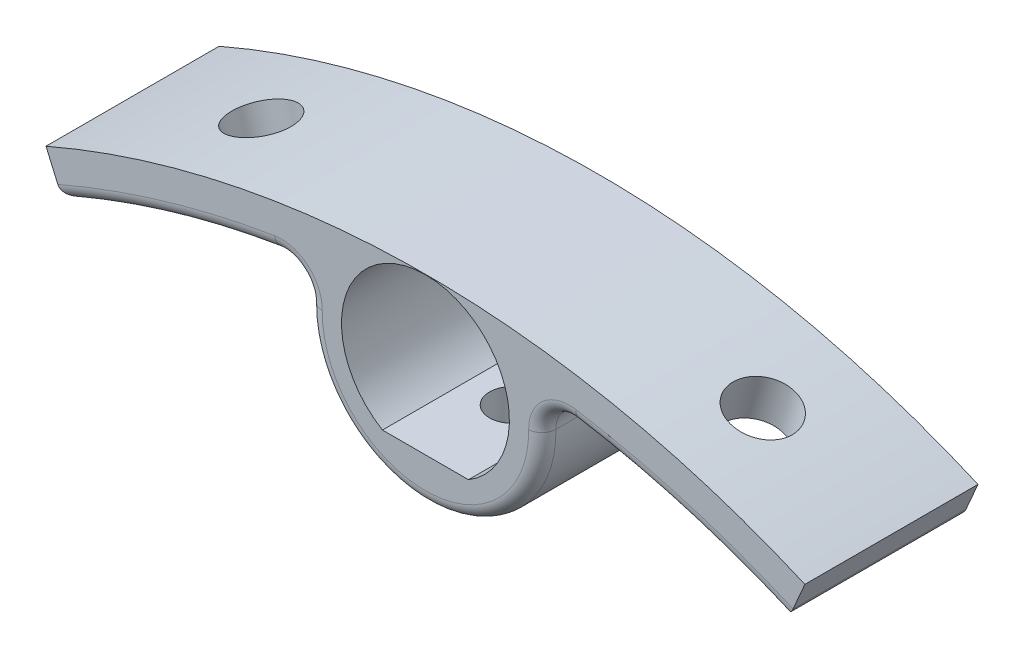
SolidWorks part; units mm, degrees
ref_plane "Front Plane" through (0, 0, 0) normal (0, 0, 1) x (1, 0, 0)
ref_plane "Top Plane" through (0, 0, 0) normal (0, 1, 0) x (1, 0, 0)
ref_plane "Right Plane" through (0, 0, 0) normal (1, 0, 0) x (0, 0, -1)
sketch "Sketch1" plane through (0, 0, 0) normal (0, 0, 1) x (1, 0, 0)
  line L0 (0, 0) -> (0, -69.85) construction
  line L1 (0, -6.1913) -> (0, -0.7937) construction
  line L2 (-2.765, -10.8267) -> (2.765, -10.8267)
  line L3 (-27.8391, -5.7875) -> (-26.5737, -8.6994)
  line L4 (27.8391, -5.7875) -> (26.5737, -8.6994)
  arc A0 (-27.8391, -5.7875) -> (27.8391, -5.7875) centre (0, -69.85) cw
  arc A1 (2.765, -10.8267) -> (-2.765, -10.8267) centre (0, -6.1913) ccw
  arc A4 (-8.1967, -3.6807) -> (8.1967, -3.6807) centre (0, -6.1913) ccw
  arc A5 (-8.1967, -3.6807) -> (-26.5737, -8.6994) centre (0, -69.85) ccw
  arc A6 (8.1967, -3.6807) -> (26.5737, -8.6994) centre (0, -69.85) cw
  point P9 (0, -14.7637)
  dimension "D1" = 69.85
  dimension "D3" = 10.033
  dimension "D4" = 5.3975
  dimension "D5" = 3.175
  dimension "D7" = 3.175
  dimension "D2" = 0.7937
  dimension "D6" = 19.05
extrude "Boss-Extrude1" add sketch "Sketch1" along normal blind 12.7
sketch "Sketch2" plane through (0, -10.8267, 0) normal (0, 1, 0) x (1, 0, 0)
  line L0 (0, 0) -> (0, -12.7) construction
  line L1 (-27.8391, -12.7) -> (27.8391, -12.7) construction
  circle A0 centre (0, -6.35) radius 1.651
  dimension "D1" = 3.302
extrude "Cut-Extrude1" cut sketch "Sketch2" against normal through all
sketch "Sketch3" plane through (0, -10.8267, 0) normal (0, 1, 0) x (1, 0, 0)
  line L0 (27.8391, 0) -> (-27.8391, 0) construction
  line L1 (-1.5875, 0) -> (1.5875, 0)
  line L2 (-1.5875, 0) -> (-1.5875, -12.7)
  line L3 (-1.5875, -12.7) -> (1.5875, -12.7)
  line L4 (1.5875, 0) -> (1.5875, -12.7)
  line L5 (-27.8391, -12.7) -> (27.8391, -12.7) construction
  point P8 (0, 0)
  dimension "D1" = 3.175
extrude "Cut-Extrude2" [suppressed] cut sketch "Sketch3" along normal through all
ref_plane "Plane1" through (0.3665, -1.3422, 0) normal (-0.2634, 0.9647, 0) x (0.9647, 0.2634, 0)
sketch "Sketch4" plane through (0.3665, -1.3422, 0) normal (-0.2634, 0.9647, 0) x (0.9647, 0.2634, 0)
  line L0 (-27.9268, -6.35) -> (-8.8768, -6.35) construction
  line L1 (-27.9268, -12.7) -> (-27.9268, 0) construction
  line L2 (-8.8768, -12.7) -> (-8.8768, 0) construction
  circle A0 centre (-18.4018, -6.35) radius 2.253
  dimension "D1" = 4.506
extrude "Cut-Extrude3" cut sketch "Sketch4" along normal through all
mirror "Mirror1" about plane through (0, 0, 0) normal (1, 0, 0) of "Cut-Extrude3"
fillet "Fillet1" radius 2 2 edges at (-8.1967, -3.6807, 6.35) (8.1967, -3.6807, 6.35)
fillet "Fillet2" radius 1 12 edges at (-18.8784, -5.9034, 0) (-9.2675, -4.5284, 0) (0, -14.7637, 0) (9.2675, -4.5284, 0) (-18.8784, -5.9034, 12.7) (-9.2675, -4.5284, 12.7) (0, -14.7637, 12.7) (9.2675, -4.5284, 12.7) (-26.5737, -8.6994, 6.35) (18.8784, -5.9034, 0) (26.5737, -8.6994, 6.35) (18.8784, -5.9034, 12.7)
sketch "Sketch5" plane through (0, 0, 12.7) normal (0, 0, 1) x (1, 0, 0)
  line L0 (-3.1553, -11.4812) -> (3.1553, -11.4812)
  arc A2 (3.1553, -11.4812) -> (-3.1553, -11.4812) centre (0, -6.1913) ccw
  arc A3 (3.1553, -11.4812) -> (-3.1553, -11.4812) centre (0, -6.1913) ccw
  dimension "D1" = 0.762
extrude "Cut-Extrude4" cut sketch "Sketch5" against normal through all
